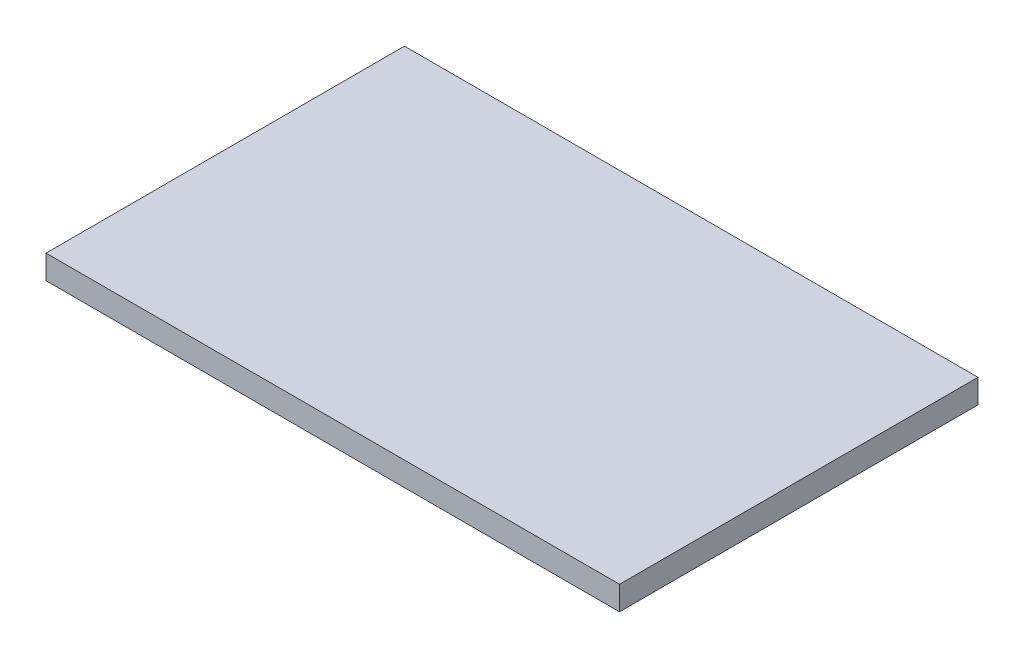
SolidWorks part; units mm, degrees
ref_plane "Front" through (0, 0, 0) normal (0, 0, 1) x (1, 0, 0)
ref_plane "Top" through (0, 0, 0) normal (0, 1, 0) x (1, 0, 0)
ref_plane "Right" through (0, 0, 0) normal (1, 0, 0) x (0, 0, -1)
sketch "Skizze1" plane through (0, 0, 0) normal (0, 1, 0) x (1, 0, 0)
  line L1 (0, 0) -> (120, 0)
  line L2 (0, 0) -> (0, 75)
  line L3 (0, 75) -> (120, 75)
  line L4 (120, 0) -> (120, 75)
  dimension "D1" = 75
  dimension "D2" = 120
extrude "Aufsatz-Linear austragen1" add sketch "Skizze1" along normal blind 5
